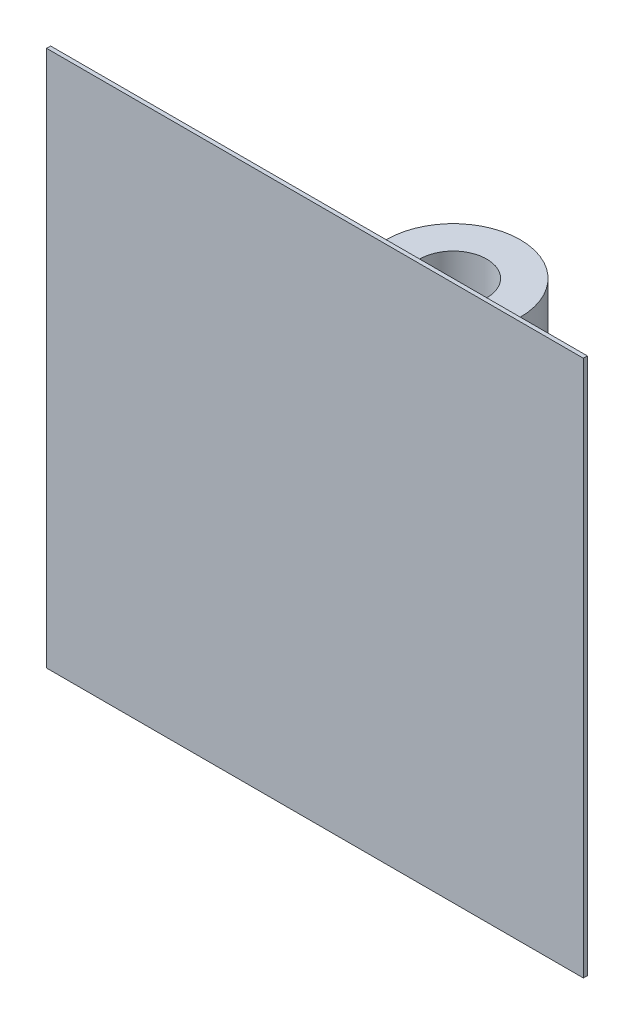
SolidWorks part; units mm, degrees
material "Aleación 1060"
ref_plane "Alzado" through (0, 0, 0) normal (0, 0, 1) x (1, 0, 0)
ref_plane "Planta" through (0, 0, 0) normal (0, 1, 0) x (1, 0, 0)
ref_plane "Vista lateral" through (0, 0, 0) normal (1, 0, 0) x (0, 0, -1)
sketch "Croquis1" plane through (0, 0, 0) normal (0, 0, 1) x (1, 0, 0)
  line L1 (-20, 20) -> (20, 20)
  line L2 (-20, 20) -> (-20, -20)
  line L3 (-20, -20) -> (20, -20)
  line L4 (20, 20) -> (20, -20)
  line L5 (-20, 20) -> (20, -20) construction
  line L6 (-20, -20) -> (20, 20) construction
  point P0 (0, 0)
  dimension "D1" = 40
  dimension "D2" = 40
extrude "Saliente-Extruir1" add sketch "Croquis1" along normal blind 0.3 contours L1 L4 L3 L2
sketch "Croquis2" plane through (0, 0, 0) normal (0, 1, 0) x (1, 0, 0)
  line L0 (0, 0) -> (0, 10) construction
  line L1 (-20, 0) -> (20, 0) construction
  line L2 (-5, 10) -> (-5, 0)
  line L3 (5, 10) -> (5, 0)
  line L4 (-5, 0) -> (5, 0)
  circle A0 centre (0, 10) radius 2.5
  arc A1 (5, 10) -> (-5, 10) centre (0, 10) ccw
  dimension "D2" = 5
  dimension "D3" = 10
  dimension "D1" = 10
extrude "Saliente-Extruir2" add sketch "Croquis2" along normal blind 10 and the other way blind 10
sketch "Croquis3" plane through (0, 0, 0) normal (0, 1, 0) x (1, 0, 0)
  line L1 (-7.0281, 16) -> (7.0281, 16)
  line L2 (-7.0281, 16) -> (-7.0281, 4)
  line L3 (-7.0281, 4) -> (7.0281, 4)
  line L4 (7.0281, 16) -> (7.0281, 4)
  line L5 (-7.0281, 16) -> (7.0281, 4) construction
  line L6 (-7.0281, 4) -> (7.0281, 16) construction
  line L7 (-20, 0) -> (20, 0) construction
  point P0 (0, 10)
  dimension "D1" = 4
extrude "Cortar-Extruir1" cut sketch "Croquis3" against normal blind 2.5 and the other way blind 2.5
